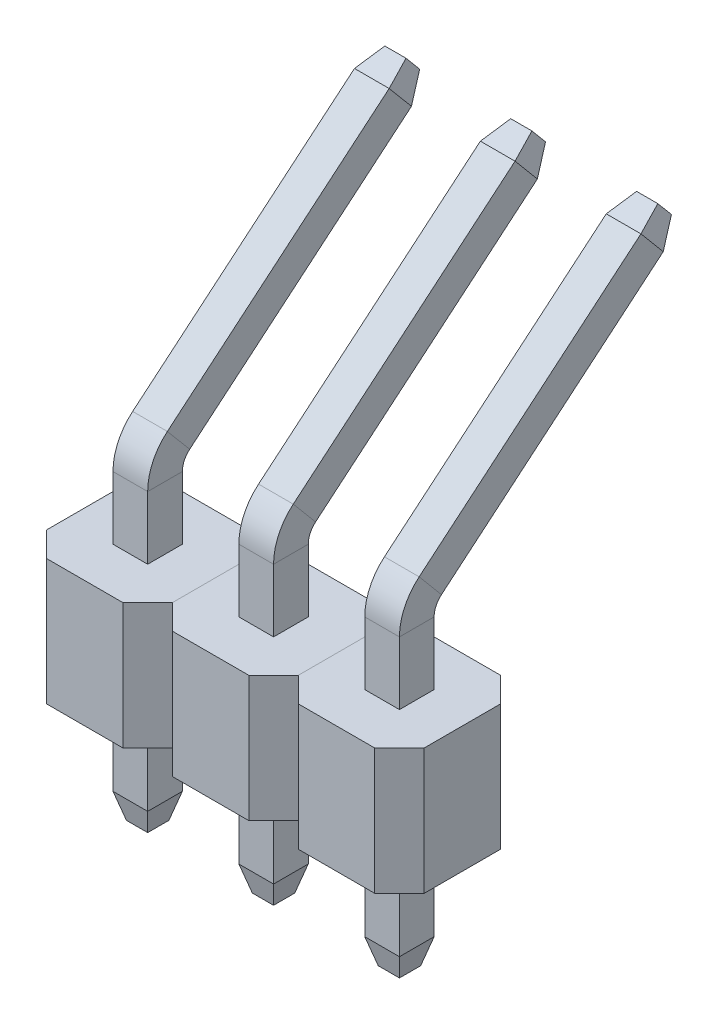
SolidWorks part; units mm, degrees
ref_plane "Front Plane" through (0, 0, 0) normal (0, 0, 1) x (1, 0, 0)
ref_plane "Top Plane" through (0, 0, 0) normal (0, 1, 0) x (1, 0, 0)
ref_plane "Right Plane" through (0, 0, 0) normal (1, 0, 0) x (0, 0, -1)
sketch "Sketch3" plane through (0, 0, 0) normal (0, 1, 0) x (1, 0, 0)
  line L1 (-1.27, 1.27) -> (1.27, 1.27)
  line L2 (-1.27, 1.27) -> (-1.27, -1.27)
  line L3 (-1.27, -1.27) -> (1.27, -1.27)
  line L4 (1.27, 1.27) -> (1.27, -1.27)
  line L5 (-1.27, 1.27) -> (1.27, -1.27) construction
  line L6 (-1.27, -1.27) -> (1.27, 1.27) construction
  line L7 (0.3175, -0.3175) -> (-0.3175, -0.3175)
  line L8 (0.3175, -0.3175) -> (0.3175, 0.3175)
  line L9 (0.3175, 0.3175) -> (-0.3175, 0.3175)
  line L10 (-0.3175, -0.3175) -> (-0.3175, 0.3175)
  line L11 (0.3175, -0.3175) -> (-0.3175, 0.3175) construction
  line L12 (0.3175, 0.3175) -> (-0.3175, -0.3175) construction
  point P0 (0, 0)
  point P7 (0, 0)
  dimension "D1" = 2.54
  dimension "D2" = 0.635
extrude "Boss-Extrude1" add sketch "Sketch3" along normal mid plane 2.54
chamfer "Chamfer1" distance 0.5 angle 45 4 edges at (-1.27, 0, 1.27) (-1.27, 0, -1.27) (1.27, 0, -1.27) (1.27, 0, 1.27)
sketch "Sketch5" plane through (0, 1.27, 0) normal (0, 1, 0) x (1, 0, 0)
  line L1 (0.35, -0.35) -> (-0.35, -0.35)
  line L2 (0.35, -0.35) -> (0.35, 0.35)
  line L3 (0.35, 0.35) -> (-0.35, 0.35)
  line L4 (-0.35, -0.35) -> (-0.35, 0.35)
  line L5 (0.35, -0.35) -> (-0.35, 0.35) construction
  line L6 (0.35, 0.35) -> (-0.35, -0.35) construction
  point P0 (0, 0)
  dimension "D1" = 0.7
sketch "Sketch9" plane through (0, 0, 0) normal (1, 0, 0) x (0, 0, -1)
  line L0 (0, -3.048) -> (0, 2.54)
  line L1 (0.2722, 3.1237) -> (4.7474, 6.8789)
  line L2 (-0.35, 1.27) -> (0.35, 1.27) construction
  line L4 (-0.77, 1.27) -> (0.77, 1.27) construction
  arc A0 (0, 2.54) -> (0.2722, 3.1237) centre (0.762, 2.54) cw
  dimension "D2" = 0.762
  dimension "D1" = 1.27
  dimension "D3" = 50
  dimension "D4" = 5.842
  dimension "D5" = 4.318
sweep "Sweep1" add profiles "Sketch5" path "Sketch9"
sketch "Sketch10" plane through (0, 5.1798, -6.1731) normal (0, 0.6428, -0.766) x (1, 0, 0)
  line L4 (-0.35, -1.8679) -> (-0.35, -2.5679)
  line L5 (-0.35, -2.5679) -> (0.35, -2.5679)
  line L6 (0.35, -2.5679) -> (0.35, -1.8679)
  line L7 (0.35, -1.8679) -> (-0.35, -1.8679)
  line L8 (-0.35, -1.8679) -> (-0.35, -2.5679)
  line L9 (-0.35, -2.5679) -> (0.35, -2.5679)
  line L10 (0.35, -2.5679) -> (0.35, -1.8679)
  line L11 (0.35, -1.8679) -> (-0.35, -1.8679)
  dimension "D1" = 0
extrude "Boss-Extrude5" add sketch "Sketch10" along normal blind 0.508 draft 15
sketch "Sketch11" plane through (0, -3.048, 0) normal (0, -1, 0) x (1, 0, 0)
  line L4 (-0.35, 0.35) -> (-0.35, -0.35)
  line L5 (-0.35, -0.35) -> (0.35, -0.35)
  line L6 (0.35, -0.35) -> (0.35, 0.35)
  line L7 (0.35, 0.35) -> (-0.35, 0.35)
  line L8 (-0.35, 0.35) -> (-0.35, -0.35)
  line L9 (-0.35, -0.35) -> (0.35, -0.35)
  line L10 (0.35, -0.35) -> (0.35, 0.35)
  line L11 (0.35, 0.35) -> (-0.35, 0.35)
  dimension "D1" = 0
extrude "Boss-Extrude6" add sketch "Sketch11" along normal blind 0.508 draft 15
pattern_linear "LPattern1" count 3 spacing 2.54 along (1, 0, 0) of "Boss-Extrude1"
